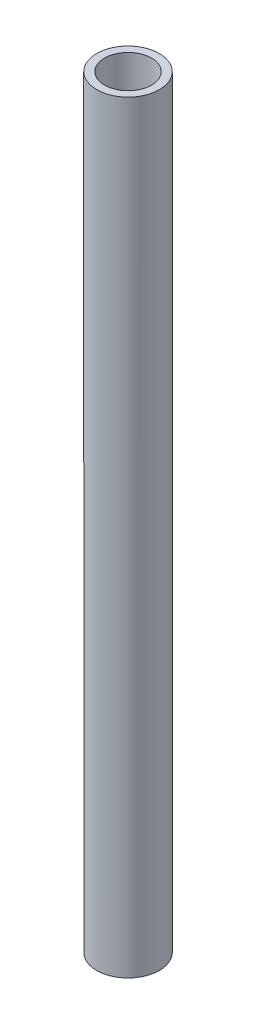
SolidWorks part; units mm, degrees
ref_plane "前视基准面" through (0, 0, 0) normal (0, 0, 1) x (1, 0, 0)
ref_plane "上视基准面" through (0, 0, 0) normal (0, 1, 0) x (1, 0, 0)
ref_plane "右视基准面" through (0, 0, 0) normal (1, 0, 0) x (0, 0, -1)
sketch "Sketch1" plane through (0, 0, 0) normal (0, 1, 0) x (1, 0, 0)
  circle A0 centre (0, 0) radius 4
  circle A1 centre (0, 0) radius 3
extrude "Boss-Extrude1" add sketch "Sketch1" along normal blind 270
sketch "Sketch2" plane through (0, 270, 0) normal (0, 1, 0) x (1, 0, 0)
  circle A0 centre (0, 0) radius 4 construction
  circle A1 centre (0, 0) radius 3 construction
  circle A2 centre (0, 0) radius 4
  circle A3 centre (0, 0) radius 3
extrude "Cut-Extrude1" cut sketch "Sketch2" against normal up to surface (172.5521 mm away)
